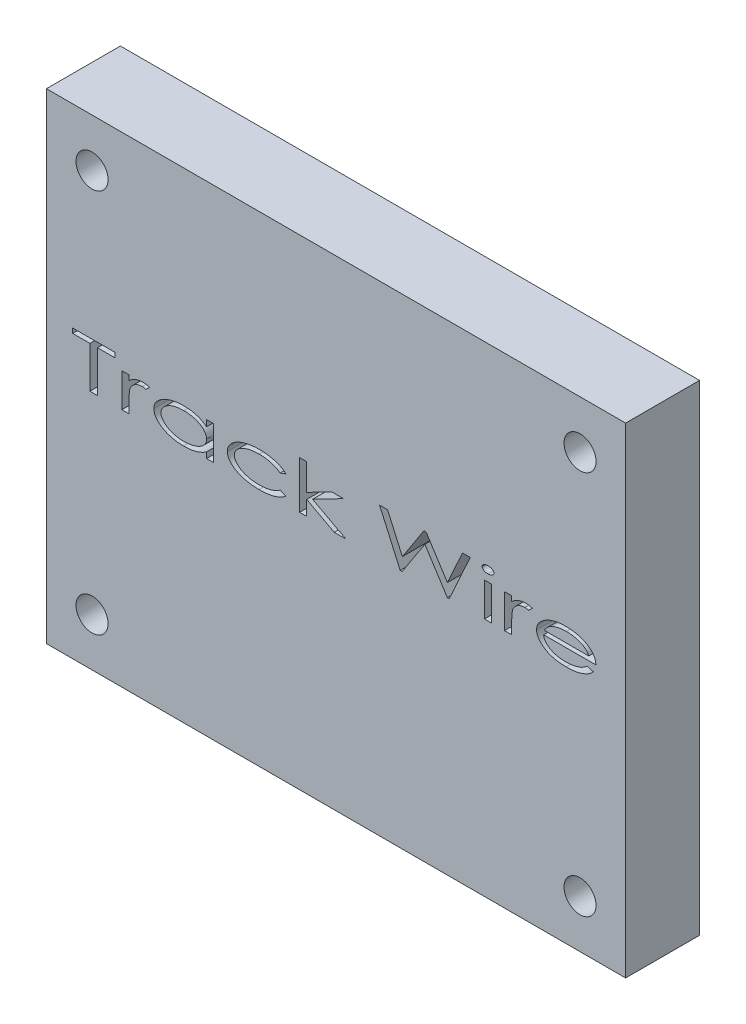
SolidWorks part; units mm, degrees
ref_plane "Front Plane" through (0, 0, 0) normal (0, 0, 1) x (1, 0, 0)
ref_plane "Top Plane" through (0, 0, 0) normal (0, 1, 0) x (1, 0, 0)
ref_plane "Right Plane" through (0, 0, 0) normal (1, 0, 0) x (0, 0, -1)
sketch "Sketch1" plane through (0, 0, 0) normal (0, 0, 1) x (1, 0, 0)
  line L1 (-102.0287, 54.4392) -> (-42.3387, 54.4392)
  line L2 (-102.0287, 54.4392) -> (-102.0287, 4.9092)
  line L3 (-102.0287, 4.9092) -> (-42.3387, 4.9092)
  line L4 (-42.3387, 54.4392) -> (-42.3387, 4.9092)
  dimension "D1" = 59.69
  dimension "D2" = 49.53
extrude "Boss-Extrude1" add sketch "Sketch1" along normal blind 7.62
sketch "Sketch2" plane through (0, 0, 7.62) normal (0, 0, 1) x (1, 0, 0)
  line L0 (-102.0287, 29.6742) -> (-42.3387, 29.6742) construction
  line L1 (-102.0287, 54.4392) -> (-102.0287, 4.9092) construction
  line L2 (-42.3387, 4.9092) -> (-42.3387, 54.4392) construction
  text T0 "Track Wire" font "Century Gothic" height in points 18
extrude "Cut-Extrude1" cut sketch "Sketch2" against normal through all
sketch "Sketch3" plane through (0, 0, 7.62) normal (0, 0, 1) x (1, 0, 0)
  line L0 (-42.3387, 54.4392) -> (-102.0287, 54.4392) construction
  line L1 (-102.0287, 54.4392) -> (-102.0287, 4.9092) construction
  line L2 (-72.1837, 54.4392) -> (-72.1837, 4.9092) construction
  line L3 (-102.0287, 4.9092) -> (-42.3387, 4.9092) construction
  line L4 (-42.3387, 29.6742) -> (-102.0287, 29.6742) construction
  line L5 (-42.3387, 4.9092) -> (-42.3387, 54.4392) construction
  circle A0 centre (-97.3297, 49.4862) radius 1.651
  circle A1 centre (-47.0377, 49.4862) radius 1.651
  circle A2 centre (-47.0377, 9.8622) radius 1.651
  circle A3 centre (-97.3297, 9.8622) radius 1.651
  dimension "D1" = 3.302
  dimension "D2" = 4.953
  dimension "D3" = 4.699
extrude "Cut-Extrude2" cut sketch "Sketch3" against normal through all
equation "\"D1@Boss-Extrude1\"=0.3"
